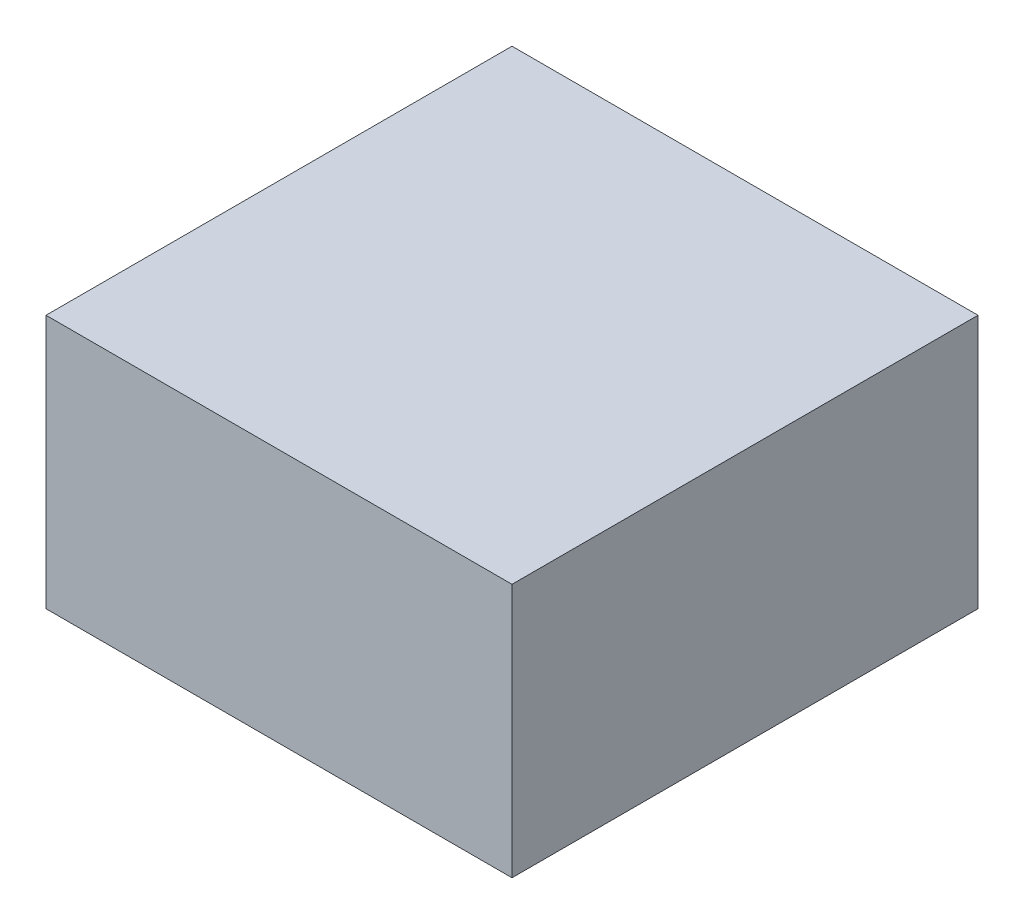
SolidWorks part; units mm, degrees
ref_plane "Front Plane" through (0, 0, 0) normal (0, 0, 1) x (1, 0, 0)
ref_plane "Top Plane" through (0, 0, 0) normal (0, 1, 0) x (1, 0, 0)
ref_plane "Right Plane" through (0, 0, 0) normal (1, 0, 0) x (0, 0, -1)
sketch "Sketch1" plane through (0, 0, 0) normal (0, 1, 0) x (1, 0, 0)
  line L1 (0, 0) -> (220, 0)
  line L2 (0, 0) -> (0, 220)
  line L3 (0, 220) -> (220, 220)
  line L4 (220, 0) -> (220, 220)
  dimension "D1" = 220
  dimension "D2" = 220
extrude "Boss-Extrude1" add sketch "Sketch1" against normal blind 120
